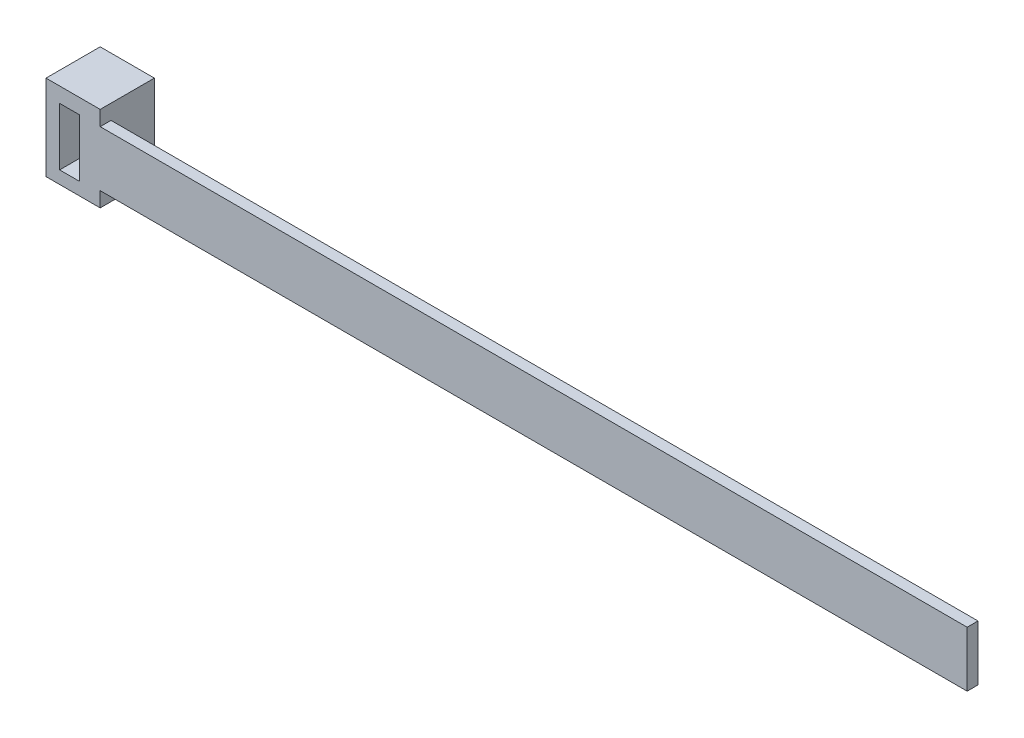
SolidWorks part; units mm, degrees
material "Nylon 6/10"
ref_plane "Front Plane" through (0, 0, 0) normal (0, 0, 1) x (1, 0, 0)
ref_plane "Top Plane" through (0, 0, 0) normal (0, 1, 0) x (1, 0, 0)
ref_plane "Right Plane" through (0, 0, 0) normal (1, 0, 0) x (0, 0, -1)
sketch "Sketch1" plane through (0, 0, 0) normal (0, 1, 0) x (1, 0, 0)
  line L1 (-73.0239, 9.3808) -> (-66.6739, 9.3808)
  line L2 (-73.0239, 9.3808) -> (-73.0239, 3.0308)
  line L3 (-73.0239, 3.0308) -> (-66.6739, 3.0308)
  line L4 (-66.6739, 9.3808) -> (-66.6739, 4.3008)
  line L5 (-66.6739, 3.0308) -> (34.9261, 3.0308)
  line L7 (-66.6739, 4.3008) -> (34.9261, 4.3008)
  line L8 (34.9261, 3.0308) -> (34.9261, 4.3008)
  point P7 (0, 0)
  dimension "D1" = 6.35
  dimension "D2" = 6.35
  dimension "D3" = 1.27
  dimension "D4" = 101.6
extrude "Boss-Extrude1" add sketch "Sketch1" along normal mid plane 10
sketch "Sketch2" plane through (0, 0, -9.3808) normal (0, 0, -1) x (-1, 0, 0)
  line L1 (71.4239, 3.2345) -> (69.1173, 3.2345)
  line L2 (71.4239, 3.2345) -> (71.4239, -3.5155)
  line L3 (71.4239, -3.5155) -> (69.1173, -3.5155)
  line L4 (69.1173, 3.2345) -> (69.1173, -3.5155)
extrude "Cut-Extrude1" cut sketch "Sketch2" against normal up to next
sketch "Sketch3" plane through (0, 0, -4.3008) normal (0, 0, -1) x (-1, 0, 0)
  line L0 (-34.9261, 5) -> (-34.9261, -5) construction
  line L1 (66.6739, 5) -> (-34.9261, 5)
  line L2 (66.6739, 5) -> (66.6739, 3.2467)
  line L3 (66.6739, 3.2467) -> (-34.9261, 3.2467)
  line L4 (-34.9261, 5) -> (-34.9261, 3.2467)
  line L5 (66.6739, 5) -> (66.6739, -5) construction
  line L6 (-34.9261, -5) -> (66.6739, -5)
  line L7 (-34.9261, -5) -> (-34.9261, -3.2467)
  line L8 (-34.9261, -3.2467) -> (66.6739, -3.2467)
  line L9 (66.6739, -5) -> (66.6739, -3.2467)
extrude "Cut-Extrude2" cut sketch "Sketch3" against normal up to next
